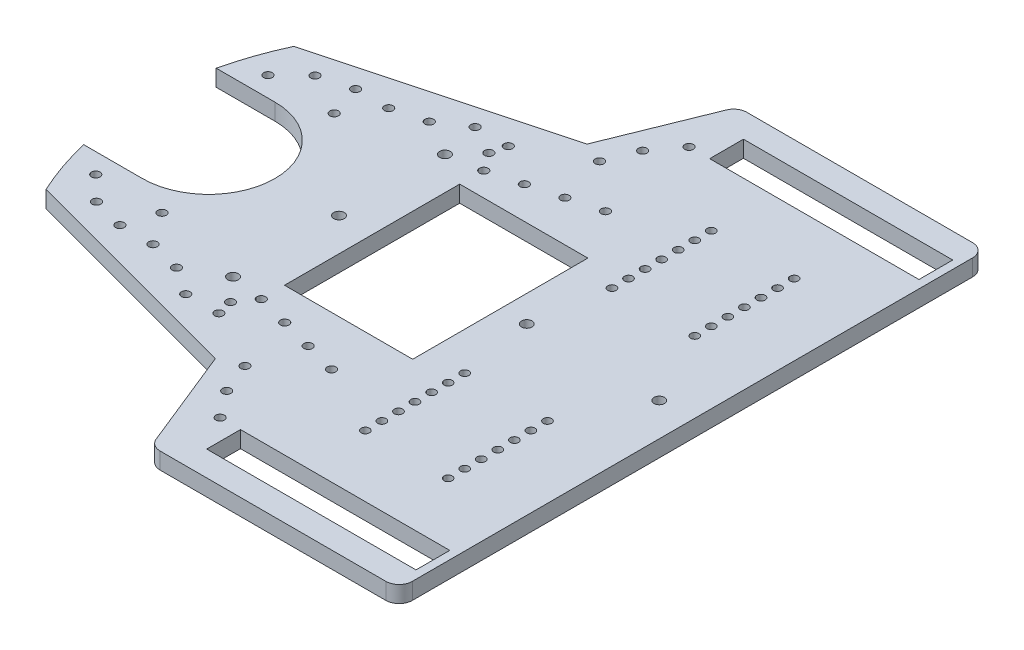
SolidWorks part; units mm, degrees
ref_plane "Front Plane" through (0, 0, 0) normal (0, 0, 1) x (1, 0, 0)
ref_plane "Top Plane" through (0, 0, 0) normal (0, 1, 0) x (1, 0, 0)
ref_plane "Right Plane" through (0, 0, 0) normal (1, 0, 0) x (0, 0, -1)
sketch "Sketch1" plane through (0, 0, 0) normal (0, 1, 0) x (1, 0, 0)
  line L0 (0, -112.5) -> (0, 0) construction
  line L1 (-3.175, 112.5) -> (95.25, 112.5)
  line L3 (-3.175, -112.5) -> (95.25, -112.5)
  line L4 (95.25, 112.5) -> (95.25, -112.5)
  line L5 (0, 0) -> (0, 112.5) construction
  arc A0 (-3.175, 112.5) -> (-3.175, -112.5) centre (-3.175, 0) ccw
  dimension "D1" = 95.25
  dimension "D4" = 112.5
  dimension "D2" = 3.175
  dimension "D3" = 225
extrude "Boss-Extrude1" add sketch "Sketch1" against normal blind 6.35
sketch "Sketch2" plane through (0, 0, 0) normal (0, 1, 0) x (1, 0, 0)
  line L0 (36.144, -66.3448) -> (36.144, -59.9948) construction
  line L1 (52.019, 0) -> (52.019, -89.9668) construction
  line L2 (11.887, -89.9668) -> (92.151, -89.9668)
  line L3 (11.887, -89.9668) -> (11.887, -102.9208)
  line L4 (11.887, -102.9208) -> (92.151, -102.9208)
  line L5 (92.151, -89.9668) -> (92.151, -102.9208)
  line L6 (11.887, 89.9668) -> (92.151, 89.9668)
  line L7 (11.887, 89.9668) -> (11.887, 102.9208)
  line L8 (11.887, 102.9208) -> (92.151, 102.9208)
  line L9 (92.151, 89.9668) -> (92.151, 102.9208)
  line L10 (52.019, 0) -> (52.019, 89.9668) construction
  line L11 (36.144, -59.9948) -> (36.144, -53.6448) construction
  line L12 (36.144, -53.6448) -> (36.144, -47.2948) construction
  line L13 (36.144, -47.2948) -> (36.144, -40.9448) construction
  line L14 (36.144, -40.9448) -> (36.144, -34.5948) construction
  line L15 (36.144, -34.5948) -> (36.144, -28.2448) construction
  line L16 (67.894, -66.3448) -> (67.894, -59.9948) construction
  line L17 (67.894, -59.9948) -> (67.894, -53.6448) construction
  line L18 (67.894, -53.6448) -> (67.894, -47.2948) construction
  line L19 (67.894, -47.2948) -> (67.894, -40.9448) construction
  line L20 (67.894, -40.9448) -> (67.894, -34.5948) construction
  line L21 (67.894, -34.5948) -> (67.894, -28.2448) construction
  line L22 (36.144, -66.3448) -> (67.894, -66.3448) construction
  line L23 (36.144, -28.2448) -> (67.894, -28.2448) construction
  line L24 (36.144, 28.2448) -> (36.144, 34.5948) construction
  line L25 (36.144, 34.5948) -> (36.144, 40.9448) construction
  line L26 (36.144, 40.9448) -> (36.144, 47.2948) construction
  line L27 (36.144, 47.2948) -> (36.144, 53.6448) construction
  line L28 (36.144, 53.6448) -> (36.144, 59.9948) construction
  line L29 (36.144, 59.9948) -> (36.144, 66.3448) construction
  line L30 (67.894, 28.2448) -> (67.894, 34.5948) construction
  line L31 (67.894, 34.5948) -> (67.894, 40.9448) construction
  line L32 (67.894, 40.9448) -> (67.894, 47.2948) construction
  line L33 (67.894, 47.2948) -> (67.894, 53.6448) construction
  line L34 (67.894, 53.6448) -> (67.894, 59.9948) construction
  line L35 (67.894, 59.9948) -> (67.894, 66.3448) construction
  line L36 (36.144, 66.3448) -> (67.894, 66.3448) construction
  line L37 (36.144, 28.2448) -> (67.894, 28.2448) construction
  line L38 (36.144, 47.2948) -> (52.019, 47.2948) construction
  line L39 (52.019, 47.2948) -> (67.894, 47.2948) construction
  line L40 (0, -112.5) -> (0, 112.5) construction
  line L41 (0, 0) -> (52.019, 0) construction
  line L42 (95.25, 112.5) -> (-3.175, 112.5) construction
  line L43 (-3.175, -112.5) -> (95.25, -112.5) construction
  line L44 (95.25, -112.5) -> (95.25, 112.5) construction
  circle A1 centre (36.144, -66.3448) radius 1.5875
  circle A2 centre (36.144, -59.9948) radius 1.5875
  circle A3 centre (36.144, -53.6448) radius 1.5875
  circle A4 centre (36.144, -47.2948) radius 1.5875
  circle A5 centre (36.144, -40.9448) radius 1.5875
  circle A6 centre (36.144, -34.5948) radius 1.5875
  circle A7 centre (36.144, -28.2448) radius 1.5875
  circle A8 centre (67.894, -66.3448) radius 1.5875
  circle A9 centre (67.894, -59.9948) radius 1.5875
  circle A10 centre (67.894, -53.6448) radius 1.5875
  circle A11 centre (67.894, -47.2948) radius 1.5875
  circle A12 centre (67.894, -40.9448) radius 1.5875
  circle A13 centre (67.894, -34.5948) radius 1.5875
  circle A14 centre (67.894, -28.2448) radius 1.5875
  circle A15 centre (36.144, 66.3448) radius 1.5875
  circle A16 centre (36.144, 59.9948) radius 1.5875
  circle A17 centre (36.144, 53.6448) radius 1.5875
  circle A18 centre (36.144, 47.2948) radius 1.5875
  circle A19 centre (36.144, 40.9448) radius 1.5875
  circle A20 centre (36.144, 34.5948) radius 1.5875
  circle A21 centre (36.144, 28.2448) radius 1.5875
  circle A22 centre (67.894, 66.3448) radius 1.5875
  circle A23 centre (67.894, 59.9948) radius 1.5875
  circle A24 centre (67.894, 53.6448) radius 1.5875
  circle A25 centre (67.894, 47.2948) radius 1.5875
  circle A26 centre (67.894, 40.9448) radius 1.5875
  circle A27 centre (67.894, 34.5948) radius 1.5875
  circle A28 centre (67.894, 28.2448) radius 1.5875
  dimension "D6" = 3.175
  dimension "D7" = 6.35
  dimension "D8" = 15.875
  dimension "D10" = 3.175
  dimension "D1" = 12.954
  dimension "D2" = 80.264
  dimension "D3" = 179.9336
  dimension "D4" = 23.622
  dimension "D5" = 15.875
  dimension "D9" = 15.875
  dimension "D11" = 6.35
  dimension "D12" = 23.622
  dimension "D13" = 56.4896
  dimension "D14" = 205.8416
  dimension "D15" = 92.151
extrude "Cut-Extrude1" cut sketch "Sketch2" against normal through all
sketch "Sketch7" plane through (0, 0, 0) normal (0, 1, 0) x (1, 0, 0)
  line L0 (46.0375, 112.5) -> (21.5519, 33.5915) construction
  line L1 (-27.5971, 33.5915) -> (21.5519, 33.5915)
  line L2 (-27.5971, 33.5915) -> (-27.5971, -33.5915)
  line L3 (-27.5971, -33.5915) -> (21.5519, -33.5915)
  line L4 (21.5519, 33.5915) -> (21.5519, -33.5915)
  line L5 (95.25, 112.5) -> (-3.175, 112.5) construction
  line L6 (21.5519, -33.5915) -> (46.0375, -112.5) construction
  line L7 (-3.175, -112.5) -> (95.25, -112.5) construction
  line L8 (-40.2971, -40.64) -> (-40.2971, 0) construction
  line L9 (-40.2971, 0) -> (-40.2971, 40.64) construction
  line L10 (95.25, -112.5) -> (95.25, 112.5) construction
  circle A0 centre (-40.2971, 0) radius 2.032
  circle A1 centre (31.7119, 0) radius 2.032
  circle A2 centre (82.5119, 0) radius 2.032
  circle A3 centre (-40.2971, 40.64) radius 2.032
  circle A4 centre (-40.2971, -40.64) radius 2.032
  dimension "D3" = 4.064
  dimension "D5" = 40.64
  dimension "D1" = 49.149
  dimension "D2" = 67.183
  dimension "D4" = 12.7
  dimension "D7" = 10.16
  dimension "D8" = 50.8
extrude "Cut-Extrude4" cut sketch "Sketch7" against normal through all
sketch "Sketch8" plane through (0, 0, 0) normal (0, 1, 0) x (1, 0, 0)
  line L0 (-3.175, 112.5) -> (-3.175, -112.5) construction
  line L1 (-115.675, 0) -> (95.25, 0) construction
  line L2 (95.25, -112.5) -> (95.25, 112.5) construction
  line L3 (-90.2716, 25.4) -> (-229.7767, 25.4)
  line L4 (-229.7767, 25.4) -> (-229.7767, -25.4)
  line L5 (-229.7767, -25.4) -> (-90.2716, -25.4)
  line L6 (-105.3846, 12.065) -> (-105.3846, -12.065) construction
  line L7 (-105.3846, -12.065) -> (-75.1586, -12.065) construction
  line L8 (-75.1586, -12.065) -> (-75.1586, 12.065) construction
  line L9 (-75.1586, 12.065) -> (-105.3846, 12.065) construction
  arc A0 (-3.175, 112.5) -> (-3.175, -112.5) centre (-3.175, 0) ccw construction
  circle A1 centre (-100.5586, 33.02) radius 1.651
  arc A2 (-90.2716, 25.4) -> (-90.2716, -25.4) centre (-90.2716, 0) cw
  circle A3 centre (-100.5586, -33.02) radius 1.651
  circle A4 centre (-75.1586, 33.02) radius 1.651
  circle A5 centre (-75.1586, -33.02) radius 1.651
  circle A6 centre (-40.2971, 0) radius 2.032 construction
  point P12 (-3.175, 0)
  point P19 (-75.1586, 0)
  point P22 (-90.2716, 12.065)
  dimension "D2" = 87.0966
  dimension "D1" = 25.4
  dimension "D6" = 33.02
  dimension "D11" = 3.302
  dimension "D3" = 112.5
  dimension "D4" = 30.226
  dimension "D5" = 24.13
  dimension "D7" = 33.02
  dimension "D8" = 33.02
  dimension "D9" = 33.02
  dimension "D10" = 25.4
extrude "Cut-Extrude5" cut sketch "Sketch8" against normal through all
sketch "Sketch9" plane through (0, 0, 0) normal (0, 1, 0) x (1, 0, 0)
  line L0 (-105.1513, 47.5087) -> (-16.4818, 71.2677)
  line L1 (-16.4818, 71.2677) -> (15.119, 149.4824)
  line L2 (-15.9904, 149.4824) -> (-132.084, 149.4824)
  line L3 (-132.084, 149.4824) -> (-132.084, 47.5087)
  line L4 (-132.084, 47.5087) -> (-105.1513, 47.5087)
  line L5 (15.119, 149.4824) -> (-15.9904, 149.4824)
  line L6 (-162.9335, 0) -> (203.9787, 0) construction
  line L7 (-105.1513, 0) -> (-105.1513, 47.5087) construction
  line L8 (-105.1513, 47.5087) -> (176.0049, 47.5087) construction
  line L9 (-16.4818, 71.2677) -> (175.2293, 71.2677) construction
  line L10 (-105.1513, -47.5087) -> (-16.4818, -71.2677)
  line L11 (-16.4818, -71.2677) -> (15.119, -149.4824)
  line L12 (15.119, -149.4824) -> (-132.084, -149.4824)
  line L13 (-132.084, -149.4824) -> (-132.084, -47.5087)
  line L14 (-132.084, -47.5087) -> (-105.1513, -47.5087)
  line L15 (-105.1513, -47.5087) -> (203.9787, -47.5087) construction
  line L16 (-16.4818, -71.2677) -> (199.2998, -71.2677) construction
  line L17 (-105.1513, -47.5087) -> (-105.1513, 0) construction
  arc A0 (-3.175, 112.5) -> (-112.7701, 25.4) centre (-3.175, 0) ccw construction
  arc A1 (-112.7701, -25.4) -> (-3.175, -112.5) centre (-3.175, 0) ccw construction
  dimension "D1" = 47.5087
  dimension "D2" = 15
  dimension "D3" = 68
  dimension "D4" = 15
  dimension "D5" = 68
extrude "Cut-Extrude6" cut sketch "Sketch9" against normal through all
fillet "Fillet1" radius 5.08 1 edges at (0.1772, -3.175, -112.5)
fillet "Fillet2" radius 5.08 3 edges at (95.25, -3.175, -112.5) (95.25, -3.175, 112.5) (0.1772, -3.175, 112.5)
sketch "Sketch10" plane through (0, 0, 0) normal (0, 1, 0) x (1, 0, 0)
  line L0 (-149.6445, 0) -> (117.1864, 0) construction
  line L1 (-91.4014, 41.91) -> (-79.1341, 45.197) construction
  line L2 (-105.1513, 47.5087) -> (-16.4818, 71.2677) construction
  line L3 (-79.1341, 45.197) -> (-66.4341, 45.197) construction
  line L4 (-66.4341, 45.197) -> (-54.1669, 48.484) construction
  line L5 (-54.1669, 48.484) -> (-43.5765, 55.4936) construction
  line L6 (-43.5765, 55.4936) -> (-30.8765, 55.4936) construction
  line L7 (-43.5765, 55.4936) -> (-32.3631, 49.5313) construction
  line L8 (-27.4372, 42.658) -> (-15.17, 45.945) construction
  line L9 (-15.17, 45.945) -> (-2.9027, 49.232) construction
  line L10 (-2.9027, 49.232) -> (9.3645, 52.519) construction
  line L11 (-30.8765, 55.4936) -> (-27.4372, 42.658) construction
  line L12 (-27.4372, 42.658) -> (8.5586, 42.658) construction
  line L13 (-8.3676, 67.9893) -> (-3.6101, 79.7646) construction
  line L14 (-3.6101, 79.7646) -> (4.033, 89.9072) construction
  line L15 (-16.4818, 71.2677) -> (-1.1064, 109.323) construction
  line L16 (-3.6101, 79.7646) -> (1.6193, 92.7078) construction
  line L17 (-8.3676, 67.9893) -> (-16.4818, 71.2677) construction
  line L18 (-91.4014, -41.91) -> (-79.1341, -45.197) construction
  line L19 (-79.1341, -45.197) -> (-66.4341, -45.197) construction
  line L20 (-66.4341, -45.197) -> (-54.1669, -48.484) construction
  line L21 (-54.1669, -48.484) -> (-43.5765, -55.4936) construction
  line L22 (-43.5765, -55.4936) -> (-30.8765, -55.4936) construction
  line L23 (-16.4818, -71.2677) -> (-105.1513, -47.5087) construction
  line L24 (-43.5765, -55.4936) -> (-32.3631, -49.5313) construction
  line L25 (-91.4014, 41.91) -> (-91.4014, 0) construction
  line L26 (-91.4014, 0) -> (-91.4014, -41.91) construction
  line L27 (-27.4383, -42.6621) -> (-15.1711, -45.9491) construction
  line L28 (-15.1711, -45.9491) -> (-2.9038, -49.2361) construction
  line L29 (-2.9038, -49.2361) -> (9.3635, -52.5231) construction
  line L30 (-27.4383, -42.6621) -> (13.4293, -42.6621) construction
  line L31 (-30.8765, -55.4936) -> (-27.4383, -42.6621) construction
  line L32 (-8.3676, -67.9893) -> (-3.6101, -79.7646) construction
  line L33 (-3.6101, -79.7646) -> (4.033, -89.9072) construction
  line L34 (-3.6101, -79.7646) -> (0.51, -89.9621) construction
  line L35 (-1.1064, -109.323) -> (-16.4818, -71.2677) construction
  line L36 (-16.4818, -71.2677) -> (-8.3676, -67.9893) construction
  line L38 (-16.4818, 71.2677) -> (-16.4818, -71.2677) construction
  circle A0 centre (-91.4014, 41.91) radius 1.651
  circle A1 centre (-79.1341, 45.197) radius 1.651
  circle A2 centre (-66.4341, 45.197) radius 1.651
  circle A3 centre (-54.1669, 48.484) radius 1.651
  circle A4 centre (-43.5765, 55.4936) radius 1.651
  circle A5 centre (-30.8765, 55.4936) radius 1.651
  circle A6 centre (-32.3631, 49.5313) radius 1.651
  circle A7 centre (-27.4372, 42.658) radius 1.651
  circle A8 centre (-15.17, 45.945) radius 1.651
  circle A9 centre (-2.9027, 49.232) radius 1.651
  circle A10 centre (9.3645, 52.519) radius 1.651
  circle A11 centre (-8.3676, 67.9893) radius 1.651
  circle A12 centre (-3.6101, 79.7646) radius 1.651
  circle A13 centre (4.033, 89.9072) radius 1.651
  circle A14 centre (-91.4014, -41.91) radius 1.651
  circle A15 centre (-79.1341, -45.197) radius 1.651
  circle A16 centre (-66.4341, -45.197) radius 1.651
  circle A17 centre (-54.1669, -48.484) radius 1.651
  circle A18 centre (-43.5765, -55.4936) radius 1.651
  circle A19 centre (-30.8765, -55.4936) radius 1.651
  circle A20 centre (-32.3631, -49.5313) radius 1.651
  circle A21 centre (-27.4383, -42.6621) radius 1.651
  circle A22 centre (-15.1711, -45.9491) radius 1.651
  circle A23 centre (-2.9038, -49.2361) radius 1.651
  circle A24 centre (9.3635, -52.5231) radius 1.651
  circle A25 centre (-8.3676, -67.9893) radius 1.651
  circle A26 centre (-3.6101, -79.7646) radius 1.651
  circle A27 centre (4.033, -89.9072) radius 1.651
  dimension "D1" = 3.302
  dimension "D6" = 3.302
  dimension "D8" = 3.302
  dimension "D11" = 3.302
  dimension "D12" = 12.7
  dimension "D15" = 3.302
  dimension "D19" = 3.302
  dimension "D2" = 41.91
  dimension "D3" = 12.7
  dimension "D4" = 18.5
  dimension "D5" = 28
  dimension "D7" = 12.7
  dimension "D9" = 12.7
  dimension "D10" = 15
  dimension "D13" = 18.5
  dimension "D14" = 28
  dimension "D16" = 12.7
  dimension "D17" = 13.2842
  dimension "D18" = 13.2884
  dimension "D20" = 12.7
  dimension "D21" = 15
extrude "Cut-Extrude7" cut sketch "Sketch10" against normal through all
